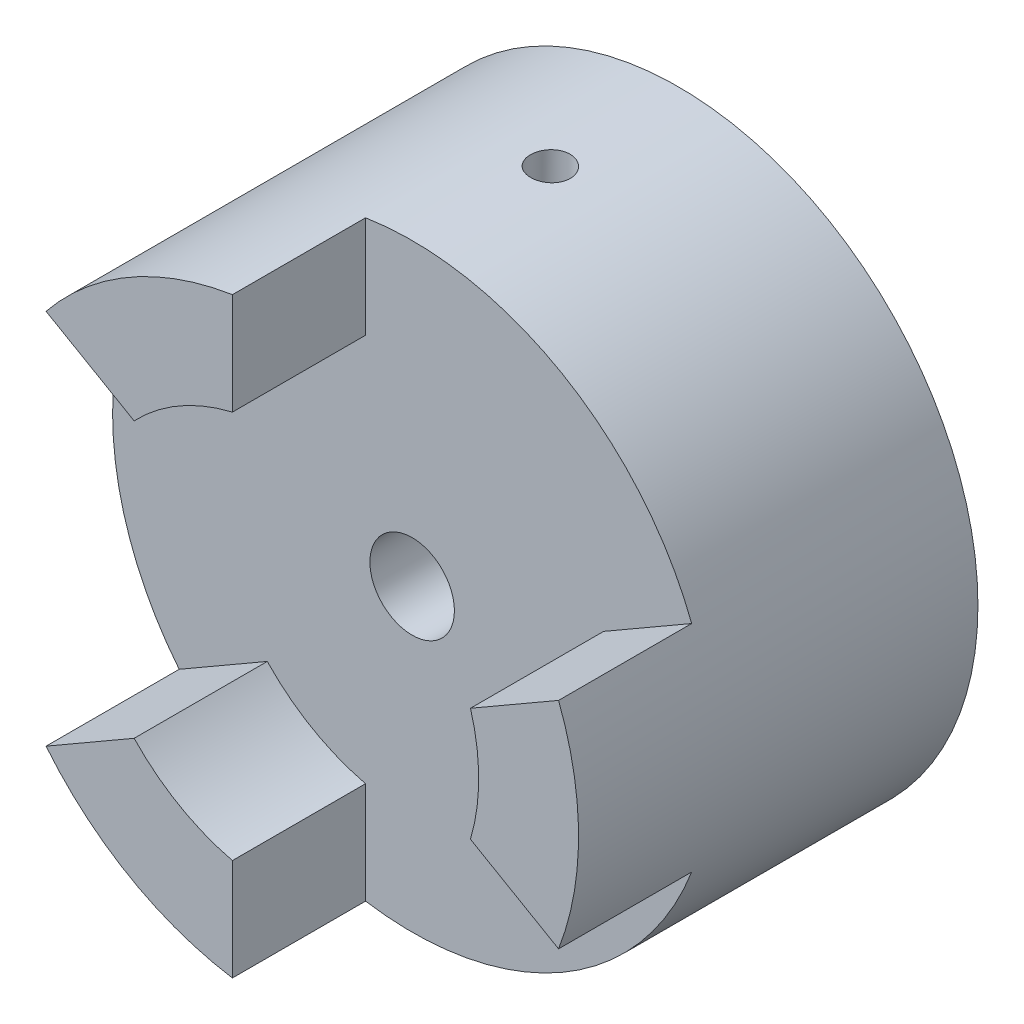
SolidWorks part; units mm, degrees
ref_plane "Front Plane" through (0, 0, 0) normal (0, 0, 1) x (1, 0, 0)
ref_plane "Top Plane" through (0, 0, 0) normal (0, 1, 0) x (1, 0, 0)
ref_plane "Right Plane" through (0, 0, 0) normal (1, 0, 0) x (0, 0, -1)
sketch "Sketch1" plane through (0, 0, 0) normal (0, 0, 1) x (1, 0, 0)
  circle A0 centre (0, 0) radius 22.5
  dimension "D1" = 45
extrude "Boss-Extrude1" add sketch "Sketch1" along normal blind 20
sketch "Sketch3" plane through (0, 0, 20) normal (0, 0, 1) x (1, 0, 0)
  circle A0 centre (0, 0) radius 3.175
  dimension "D1" = 6.35
extrude "Cut-Extrude1" cut sketch "Sketch3" against normal up to next
hole_wizard "Ø3.0mm Dowel Hole1" positions "3DSketch1" profile "Sketch4" hole size "Ø3.0" standard "ANSI Metric"
sketch3d "3DSketch1"
  point P0 (0.3326, 22.4975, 9.951)
sketch "Sketch4" plane through (0.3326, 22.4975, 9.951) normal (0, 0, 1) x (-0.9999, 0.0148, 0)
  line L0 (0, 0) -> (0, 22.9013)
  line L1 (0, 22.9013) -> (1.5, 22)
  line L2 (1.5, 22) -> (1.5, 0)
  line L5 (1.5, 0) -> (0, 0)
  line L10 (0, 22.9013) -> (-1.5, 22) construction
  line L11 (0, -6.35) -> (0, 107.95) construction
  dimension "Hole Dia." = 3
  dimension "Hole Depth" = 22
  dimension "Drill Angle" = 118
sketch "Sketch6" plane through (0, 0, 20) normal (0, 0, 1) x (1, 0, 0)
  line L0 (-3.5, 36.3116) -> (-3.5, -32.5042) construction
  line L1 (3.5, 36.3116) -> (3.5, -36.2663) construction
  line L2 (33.1967, -15.1247) -> (-26.3994, 19.2832) construction
  line L3 (29.6967, -21.1869) -> (-33.1575, 15.1021) construction
  line L4 (-29.6967, -21.1869) -> (29.8994, 13.221) construction
  line L5 (-33.1967, -15.1247) -> (29.6575, 21.1642) construction
  line L6 (-17.4984, 14.1441) -> (-10.8818, 10.3241)
  line L7 (-3.5, 22.2261) -> (-3.5, 14.586)
  line L8 (14.3818, 4.2619) -> (20.9984, 8.082)
  line L9 (20.9984, -8.082) -> (14.3818, -4.2619)
  line L10 (-3.5, -14.586) -> (-3.5, -22.2261)
  line L11 (-17.4984, -14.1441) -> (-10.8818, -10.3241)
  arc A0 (-3.5, 22.2261) -> (-17.4984, 14.1441) centre (0, 0) ccw
  arc A1 (-10.8818, -10.3241) -> (-3.5, -14.586) centre (0, 0) ccw
  arc A2 (-17.4984, -14.1441) -> (-3.5, -22.2261) centre (0, 0) ccw
  arc A3 (-3.5, 14.586) -> (-10.8818, 10.3241) centre (0, 0) ccw
  arc A4 (20.9984, -8.082) -> (20.9984, 8.082) centre (0, 0) ccw
  arc A5 (14.3818, -4.2619) -> (14.3818, 4.2619) centre (0, 0) ccw
  point P16 (0, 0)
  dimension "D3" = 30
  dimension "D4" = 45
  dimension "D1" = 7
  dimension "D2" = 3.5
extrude "Boss-Extrude3" add sketch "Sketch6" along normal blind 10
